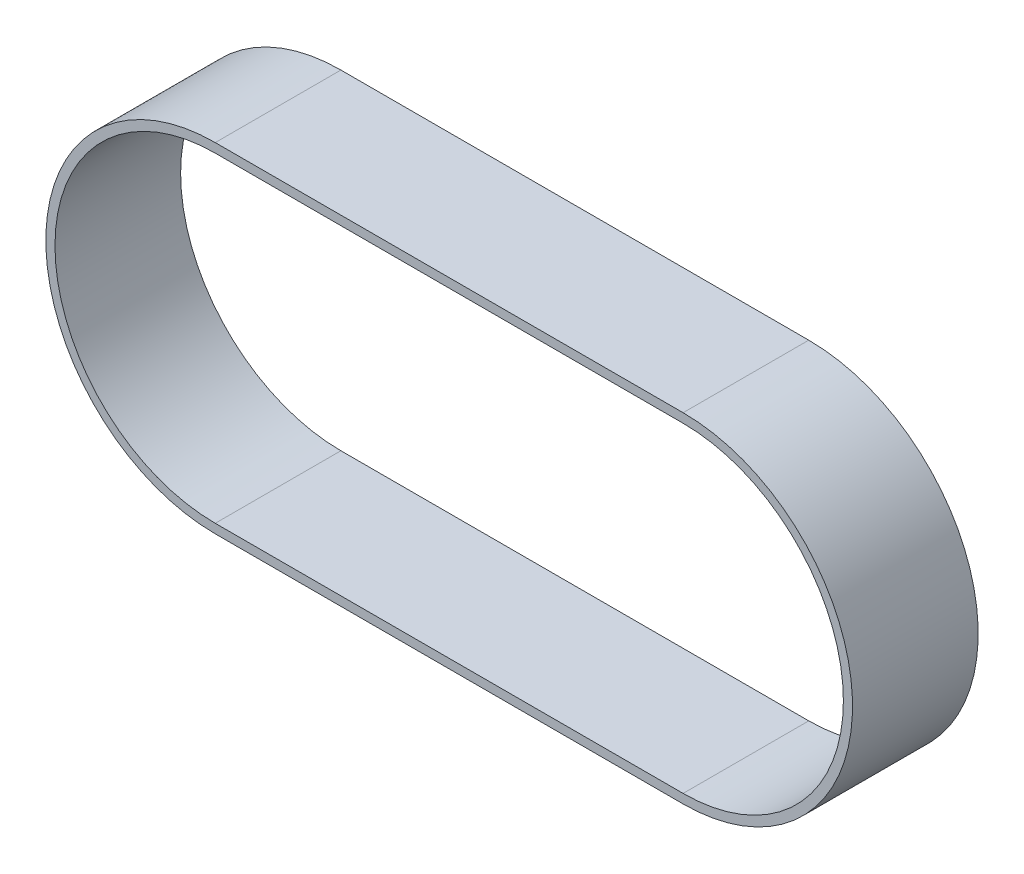
SolidWorks part; units mm, degrees
ref_plane "Alzado" through (0, 0, 0) normal (0, 0, 1) x (1, 0, 0)
ref_plane "Planta" through (0, 0, 0) normal (0, 1, 0) x (1, 0, 0)
ref_plane "Vista lateral" through (0, 0, 0) normal (1, 0, 0) x (0, 0, -1)
sketch "Croquis1" plane through (0, 0, 0) normal (0, 1, 0) x (1, 0, 0)
  line L1 (-25.6, 13.75) -> (25.6, 13.75)
  line L2 (-25.6, 13.75) -> (-25.6, 0)
  line L3 (-25.6, 0) -> (25.6, 0)
  line L4 (25.6, 13.75) -> (25.6, 0)
  dimension "D1" = 51.2
  dimension "D2" = 13.75
extrude "Saliente-Extruir1" add sketch "Croquis1" along normal blind 1
sketch "Croquis2" plane through (0, 0, 0) normal (0, 0, 1) x (1, 0, 0)
  line L0 (-25.6, 1) -> (-25.6, 17.2549) construction
  line L1 (-25.6, 1) -> (25.6, 1) construction
  line L2 (-25.6, 36.08) -> (-25.6, 37.08)
  line L3 (-25.6, 0) -> (25.6, 0) construction
  line L4 (0, 0) -> (0, 29.5) construction
  line L5 (25.6, 36.08) -> (25.6, 37.08)
  line L6 (-25.6, 1) -> (-25.6, 0)
  arc A0 (-25.6, 36.08) -> (-25.6, 1) centre (-25.6, 18.54) ccw
  arc A1 (-25.6, 37.08) -> (-25.6, 0) centre (-25.6, 18.54) ccw
  arc A2 (25.6, 37.08) -> (25.6, 0) centre (25.6, 18.54) cw
  arc A3 (25.6, 36.08) -> (25.6, 1) centre (25.6, 18.54) cw
  line M2 (25.6, 0) -> (25.6, 1)
  dimension "D1" = 17.54
  dimension "D2" = 1
extrude "Saliente-Extruir2" add sketch "Croquis2" against normal up to surface (13.75 mm away) contours L5 A3 A2 M2 | A0 L6 A1 L2 up to face at (0, 0.5, -13.75)
sketch "Croquis4" plane through (-25.6, 0, 0) normal (1, 0, 0) x (0, 0, -1)
  line L1 (0, 37.08) -> (13.75, 37.08)
  line L2 (0, 37.08) -> (0, 36.08)
  line L3 (0, 36.08) -> (13.75, 36.08)
  line L4 (13.75, 37.08) -> (13.75, 36.08)
extrude "Saliente-Extruir3" add sketch "Croquis4" along normal up to surface (51.2 mm away) up to face at (25.6, 36.58, -6.875)
